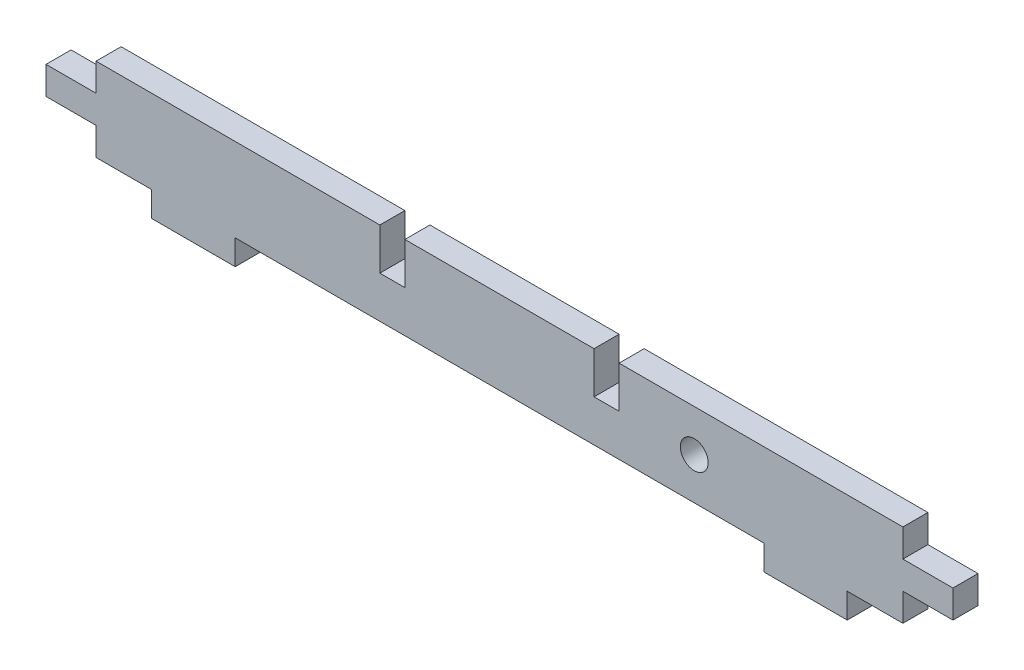
SolidWorks part; units mm, degrees
ref_plane "Front Plane" through (0, 0, 0) normal (0, 0, 1) x (1, 0, 0)
ref_plane "Top Plane" through (0, 0, 0) normal (0, 1, 0) x (1, 0, 0)
ref_plane "Right Plane" through (0, 0, 0) normal (1, 0, 0) x (0, 0, -1)
sketch "Model" plane through (0, 0, 0) normal (0, 0, 1) x (1, 0, 0)
  line L32 (0, 0) -> (0, 30) construction
  line L33 (-145, 0) -> (-125, 0)
  line L34 (-145, 0) -> (-145, 10)
  line L35 (-145, 30) -> (-43, 30)
  line L36 (145, 0) -> (145, 10)
  line L37 (-145, 20) -> (-145, 30)
  line L38 (95, 0) -> (95, -9)
  line L39 (-125, 0) -> (-125, -9)
  line L40 (-125, -9) -> (-95, -9)
  line L41 (-95, 0) -> (-95, -9)
  line L42 (-145, 10) -> (-163, 10)
  line L43 (-95, 0) -> (95, 0)
  line L44 (-145, 20) -> (-163, 20)
  line L45 (-163, 10) -> (-163, 20)
  line L46 (125, -9) -> (95, -9)
  line L47 (125, 0) -> (125, -9)
  line L48 (163, 10) -> (163, 20)
  line L49 (145, 20) -> (163, 20)
  line L50 (145, 10) -> (163, 10)
  line L51 (125, 0) -> (145, 0)
  line L52 (145, 20) -> (145, 30)
  line L53 (-34, 30) -> (34, 30)
  line L54 (43, 30) -> (43, 15)
  line L55 (-43, 30) -> (-43, 15)
  line L56 (-43, 15) -> (-34, 15)
  line L57 (-34, 30) -> (-34, 15)
  line L58 (43, 15) -> (34, 15)
  line L59 (34, 30) -> (34, 15)
  line L60 (43, 30) -> (145, 30)
  circle A0 centre (70, 15) radius 5
  dimension "D10" = 10
  dimension "D2" = 9
  dimension "D4" = 30
  dimension "D8" = 10
  dimension "D9" = 18
  dimension "D13" = 290
  dimension "D14" = 30
  dimension "D18" = 9
  dimension "D19" = 15
  dimension "D5" = 95
  dimension "D7" = 34
  dimension "D11" = 10
  dimension "D3" = 65
extrude "Boss-Extrude1" add sketch "Model" along normal blind 9
equation "\"tab-width-small\" = 20mm ' Width of the small version of the Tab"
equation "\"tab-width-large\" = 30mm ' Width of the large version of the Tab"
equation "\"baseplate-width\" = 290mm"
equation "\"material-thickness\" = 9mm"
equation "\"D2@Model\"= \"material-thickness\""
equation "\"D9@Model\"=\"material-thickness\"*2"
equation "\"D18@Model\" = \"material-thickness\""
equation "\"D1@Boss-Extrude1\" = \"material-thickness\""
equation "\"D4@Model\"=\"tab-width-large\""
equation "\"D13@Model\"=\"baseplate-width\""
